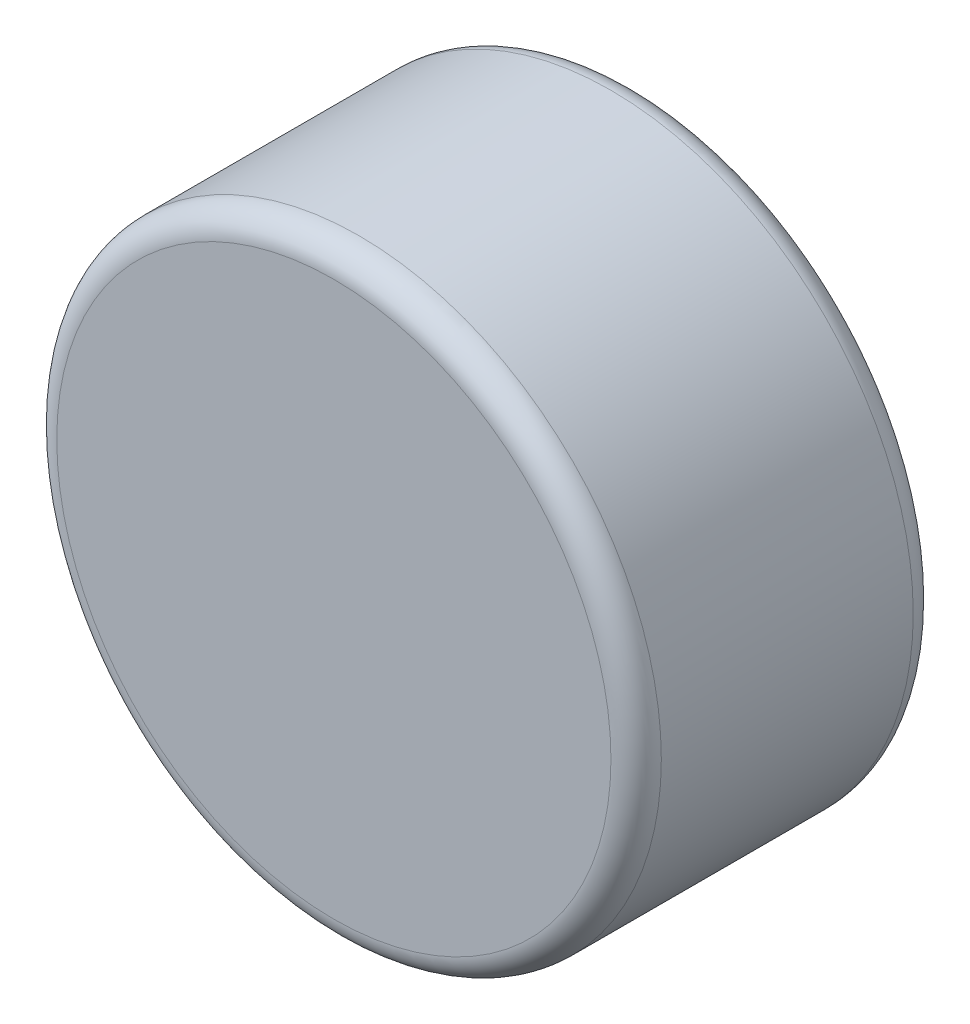
SolidWorks part; units mm, degrees
ref_plane "Front Plane" through (0, 0, 0) normal (0, 0, 1) x (1, 0, 0)
ref_plane "Top Plane" through (0, 0, 0) normal (0, 1, 0) x (1, 0, 0)
ref_plane "Right Plane" through (0, 0, 0) normal (1, 0, 0) x (0, 0, -1)
sketch "Sketch1" plane through (0, 0, 0) normal (0, 0, 1) x (1, 0, 0)
  circle A0 centre (0, 0) radius 3
  dimension "D1" = 6
extrude "Boss-Extrude1" add sketch "Sketch1" along normal mid plane 3
fillet "Fillet1" radius 0.25 2 edges at (3, 0, -1.5) (3, 0, 1.5)
